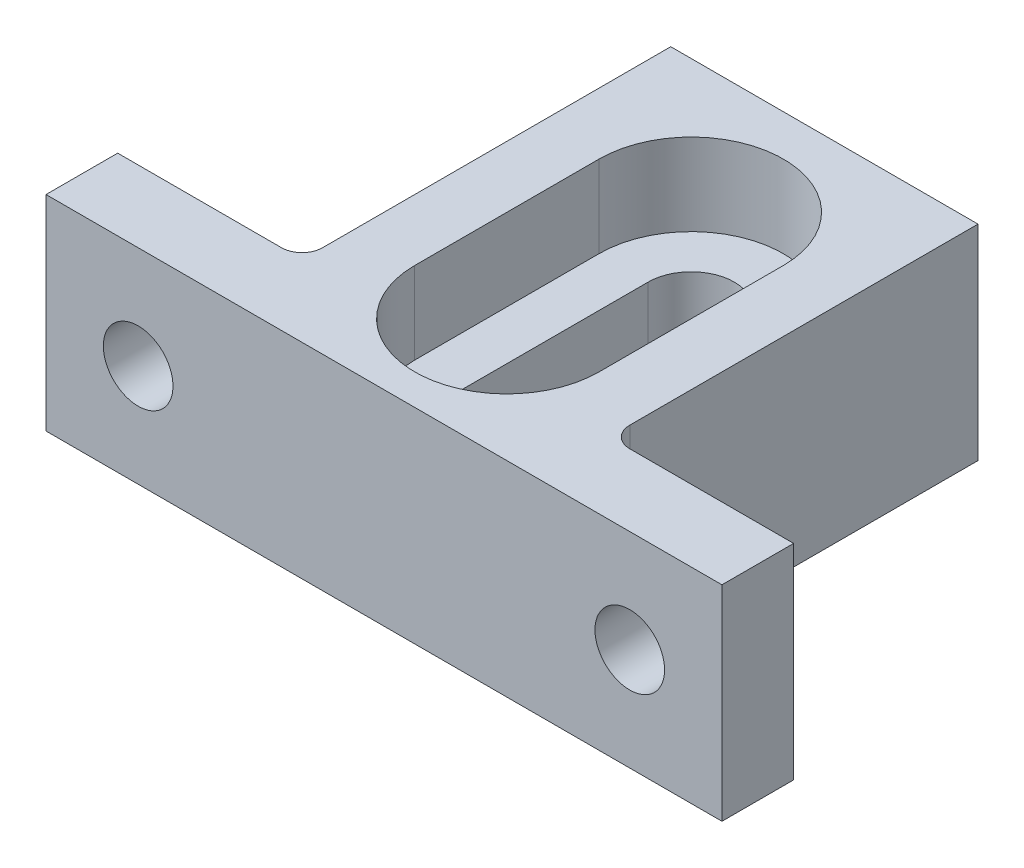
SolidWorks part; units mm, degrees
ref_plane "Front Plane" through (0, 0, 0) normal (0, 0, 1) x (1, 0, 0)
ref_plane "Top Plane" through (0, 0, 0) normal (0, 1, 0) x (1, 0, 0)
ref_plane "Right Plane" through (0, 0, 0) normal (1, 0, 0) x (0, 0, -1)
sketch "Sketch1" plane through (0, 0, 0) normal (0, 1, 0) x (1, 0, 0)
  line L0 (0, 0) -> (0, 21.5) construction
  line L1 (-7.5, 21.5) -> (7.5, 21.5)
  line L2 (7.5, 21.5) -> (7.5, 3.5)
  line L3 (7.5, 3.5) -> (16.5, 3.5)
  line L4 (16.5, 3.5) -> (16.5, 0)
  line L5 (16.5, 0) -> (-16.5, 0)
  line L6 (-16.5, 3.5) -> (-16.5, 0)
  line L7 (-7.5, 3.5) -> (-16.5, 3.5)
  line L8 (-7.5, 21.5) -> (-7.5, 3.5)
  line L9 (-12, 3.5) -> (-12, 0) construction
  line L10 (12, 3.5) -> (12, 0) construction
  dimension "D1" = 3.5
  dimension "D2" = 18
  dimension "D3" = 24
  dimension "D4" = 15
extrude "Boss-Extrude1" add sketch "Sketch1" against normal mid plane 10
sketch "Sketch3" plane through (0, 5, 0) normal (0, 1, 0) x (1, 0, 0)
  line L0 (0, 0) -> (0, 21.5) construction
  line L1 (0, 6) -> (0, 15) construction
  line L2 (0, 10.5) -> (7.5, 10.5) construction
  line L4 (4.5, 6) -> (4.5, 15)
  line L5 (-4.5, 6) -> (-4.5, 15)
  line L6 (0, 19.5) -> (7.5, 19.5) construction
  line L7 (7.5, 3.5) -> (7.5, 21.5) construction
  line L8 (7.5, 21.5) -> (-7.5, 21.5) construction
  arc A0 (4.5, 6) -> (-4.5, 6) centre (0, 6) cw
  arc A1 (4.5, 15) -> (-4.5, 15) centre (0, 15) ccw
  dimension "D1" = 9
  dimension "D3" = 9
  dimension "D2" = 2
extrude "Cut-Extrude1" cut sketch "Sketch3" against normal blind 4
sketch "Sketch4" plane through (0, 5, 0) normal (0, 1, 0) x (1, 0, 0)
  line L0 (0, 6) -> (0, 15) construction
  line L1 (0, 6) -> (0, 15) construction
  line L2 (2.1, 6) -> (2.1, 15)
  line L3 (-2.1, 6) -> (-2.1, 15)
  arc A0 (2.1, 6) -> (-2.1, 6) centre (0, 6) cw
  arc A1 (2.1, 15) -> (-2.1, 15) centre (0, 15) ccw
  dimension "D1" = 2.1
  dimension "D2" = 2.1
extrude "Cut-Extrude2" cut sketch "Sketch4" against normal through all
sketch "Sketch5" [suppressed] plane through (0, 0, -4) normal (0, 0, -1) x (-1, 0, 0)
  point P0 (-11, 0)
  point P1 (11, 0)
hole_wizard "M3 Clearance Hole1" positions "Sketch7" profile "Sketch6" hole size "M3" standard "Ansi Metric" end condition through all
sketch "Sketch7" plane through (0, 0, -3.5) normal (0, 0, -1) x (-1, 0, 0)
  point P0 (-12, 0)
  point P1 (12, 0)
sketch "Sketch6" plane through (12, 0, -3.5) normal (1, 0, 0) x (0, 1, 0)
  line L0 (0, 0) -> (0, 3.5)
  line L1 (0, 3.5) -> (1.7, 3.5)
  line L2 (1.7, 3.5) -> (1.7, 0)
  line L5 (1.7, 0) -> (0, 0)
  line L11 (0, -6.35) -> (0, 107.95) construction
  dimension "Thru Hole Dia." = 3.4
  dimension "Thru Hole Depth" = 3.5
sketch "Sketch8" plane through (0, 0, -3.5) normal (0, 0, -1) x (-1, 0, 0)
  line L0 (-7.5, 0) -> (-16.5, 0) construction
  line L1 (-13.5877, 2.75) -> (-15.1754, 0)
  line L2 (-15.1754, 0) -> (-13.5877, -2.75)
  line L3 (-13.5877, -2.75) -> (-10.4123, -2.75)
  line L4 (-10.4123, -2.75) -> (-8.8246, 0)
  line L5 (-8.8246, 0) -> (-10.4123, 2.75)
  line L6 (-10.4123, 2.75) -> (-13.5877, 2.75)
  circle A0 centre (-12, 0) radius 2.75 construction
  dimension "D1" = 5.5
fillet "Fillet1" radius 1 2 edges at (-7.5, 0, -3.5) (7.5, 0, -3.5)
